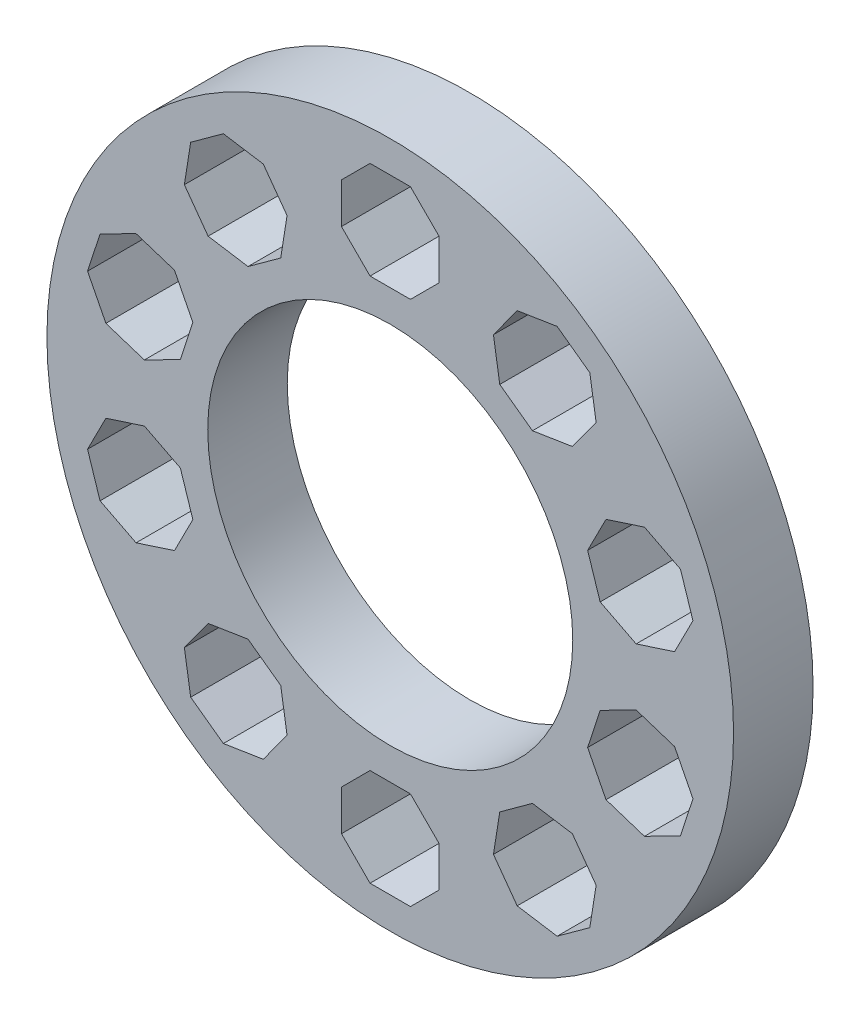
SolidWorks part; units mm, degrees
ref_plane "Alzado" through (0, 0, 0) normal (1, 0, 0) x (0, 1, 0)
ref_plane "Planta" through (0, 0, 0) normal (0, 0, 1) x (0, 1, 0)
ref_plane "Vista lateral" through (0, 0, 0) normal (0, 1, 0) x (-1, 0, 0)
sketch "Croquis1" plane through (0, 0, 0) normal (0, 0, 1) x (0, 1, 0)
  circle A0 centre (0, 0) radius 19
  circle A1 centre (0, 0) radius 10.1
  dimension "D1" = 38
  dimension "D2" = 20.2
extrude "Saliente-Extruir1" add sketch "Croquis1" along normal blind 4.4
sketch "Croquis2" plane through (0, 0, 4.4) normal (0, 0, 1) x (1, 0, 0)
  line L0 (0, 19) -> (0, 10.1) construction
  line L1 (0, 0) -> (34.5286, 0) construction
  line L2 (2.7, 13.4316) -> (2.7, 15.6684)
  line L3 (2.7, 15.6684) -> (1.1184, 17.25)
  line L4 (1.1184, 17.25) -> (-1.1184, 17.25)
  line L5 (-1.1184, 17.25) -> (-2.7, 15.6684)
  line L6 (-2.7, 15.6684) -> (-2.7, 13.4316)
  line L7 (-2.7, 13.4316) -> (-1.1184, 11.85)
  line L8 (-1.1184, 11.85) -> (1.1184, 11.85)
  line L9 (1.1184, 11.85) -> (2.7, 13.4316)
  circle A1 centre (0, 0) radius 19 construction
  circle A2 centre (0, 0) radius 10.1 construction
  circle A3 centre (0, 14.55) radius 2.7 construction
  dimension "D1" = 5.4
extrude "Cortar-Extruir1" cut sketch "Croquis2" against normal blind 4.4
pattern_circular "MatrizC1" count 10 over 360 about axis through (0, 0, 0) along (0, 0, 1) of "Cortar-Extruir1"
